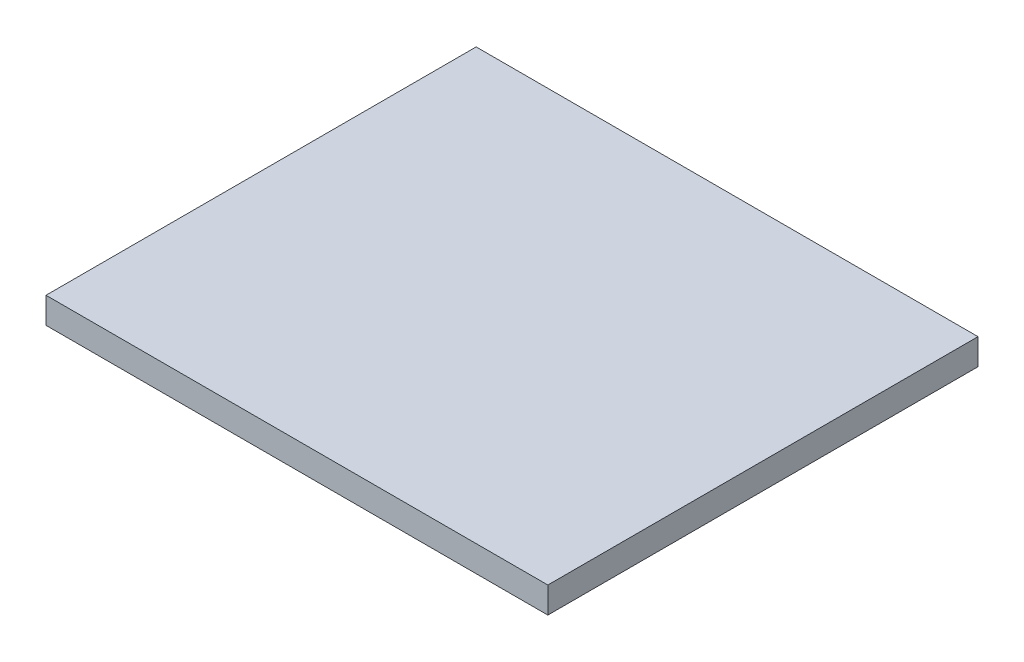
SolidWorks part; units mm, degrees
ref_plane "Front Plane" through (0, 0, 0) normal (0, 0, 1) x (1, 0, 0)
ref_plane "Top Plane" through (0, 0, 0) normal (0, 1, 0) x (1, 0, 0)
ref_plane "Right Plane" through (0, 0, 0) normal (1, 0, 0) x (0, 0, -1)
sketch "Sketch1" plane through (0, 0, 0) normal (0, 1, 0) x (1, 0, 0)
  line L1 (-19.25, 16.5) -> (19.25, 16.5)
  line L2 (-19.25, 16.5) -> (-19.25, -16.5)
  line L3 (-19.25, -16.5) -> (19.25, -16.5)
  line L4 (19.25, 16.5) -> (19.25, -16.5)
  line L5 (-19.25, 16.5) -> (19.25, -16.5) construction
  line L6 (-19.25, -16.5) -> (19.25, 16.5) construction
  point P0 (0, 0)
  dimension "D1" = 38.5
  dimension "D2" = 33
extrude "Boss-Extrude1" add sketch "Sketch1" along normal blind 2
